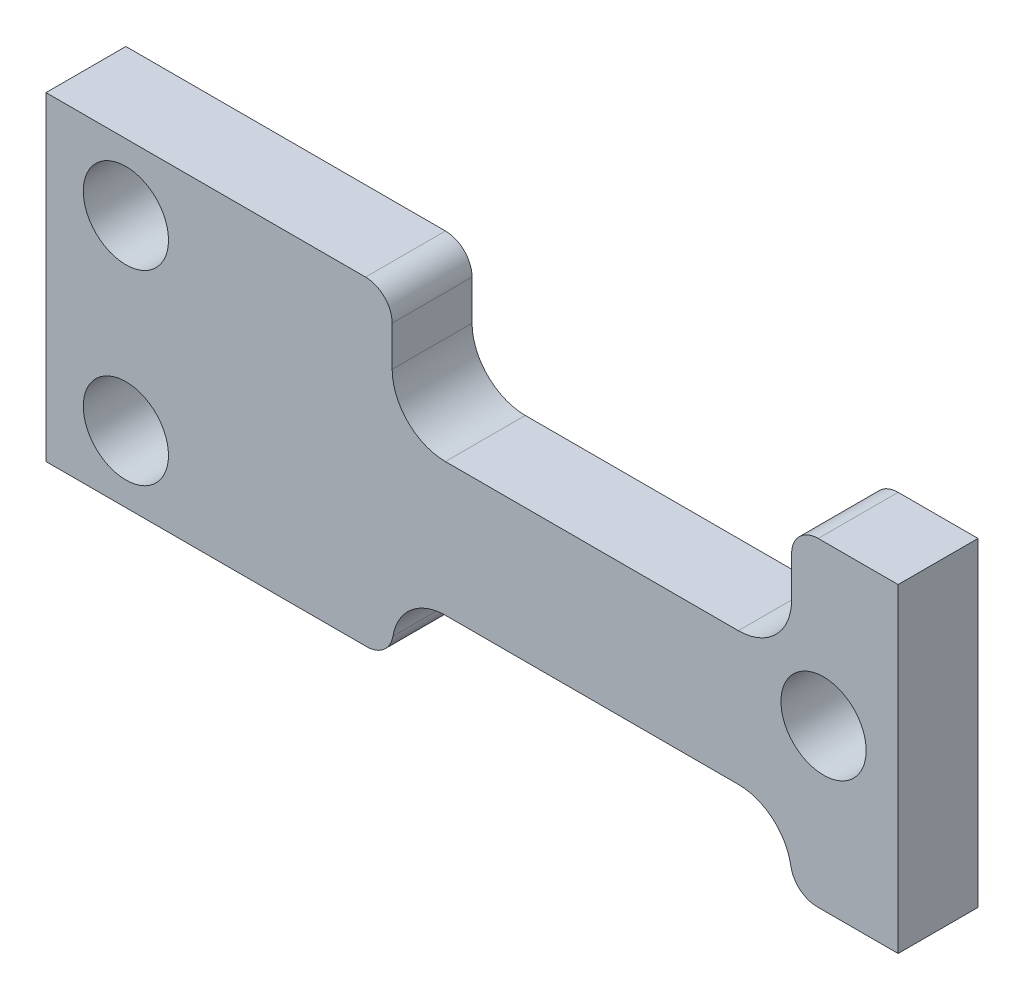
SolidWorks part; units mm, degrees
material "Thornel Mat VMA"
ref_plane "前视基准面" through (0, 0, 0) normal (0, 0, 1) x (1, 0, 0)
ref_plane "上视基准面" through (0, 0, 0) normal (0, 1, 0) x (1, 0, 0)
ref_plane "右视基准面" through (0, 0, 0) normal (1, 0, 0) x (0, 0, -1)
sketch "草图1" plane through (0, 0, 0) normal (0, 0, 1) x (1, 0, 0)
  line L0 (0, 0) -> (0, 26.8)
  line L1 (0, 26.8) -> (12, 26.8)
  line L2 (12, 26.8) -> (12, 29.8)
  line L3 (12, 29.8) -> (22, 29.8)
  line L4 (22, 29.8) -> (22, 26.8)
  line L5 (22, 26.8) -> (32, 26.8)
  line L6 (32, 26.8) -> (32, 0)
  line L7 (32, 0) -> (0, 0)
  line L9 (13, 10) -> (28, 10)
  line L10 (13, 10) -> (13, 4)
  line L11 (13, 4) -> (28, 4)
  line L12 (28, 10) -> (28, 4)
  line L13 (13, 21) -> (28, 21)
  line L14 (13, 21) -> (13, 15)
  line L15 (13, 15) -> (28, 15)
  line L16 (28, 21) -> (28, 15)
  circle A0 centre (3, 17) radius 1.6
  circle A1 centre (3, 10) radius 1.6
  dimension "D4" = 3.2
  dimension "D5" = 3
  dimension "D6" = 9.8
  dimension "D7" = 10
  dimension "D8" = 7
  dimension "D10" = 4
  dimension "D1" = 12
  dimension "D2" = 10
  dimension "D3" = 3
  dimension "D9" = 10
  dimension "D11" = 15
  dimension "D12" = 6
  dimension "D13" = 4
  dimension "D14" = 5
  dimension "D15" = 6
extrude "凸台-拉伸1" add sketch "草图1" along normal blind 3
fillet "圆角1" radius 2 8 edges at (13, 4, 1.5) (28, 4, 1.5) (28, 10, 1.5) (13, 10, 1.5) (28, 15, 1.5) (28, 21, 1.5) (13, 21, 1.5) (13, 15, 1.5)
fillet "圆角2" radius 3 2 edges at (32, 0, 1.5) (0, 0, 1.5)
sketch "草图2" plane through (0, 0, 3) normal (0, 0, 1) x (1, 0, 0)
  line L0 (0, 26.8) -> (0, 3) construction
  line L1 (0, 19.5) -> (32, 19.5)
  line L2 (0, 19.5) -> (0, 31.6123)
  line L3 (0, 31.6123) -> (32, 31.6123)
  line L4 (32, 19.5) -> (32, 31.6123)
  line L5 (32, 3) -> (32, 26.8) construction
  line L6 (3, 17) -> (3, 10) construction
  line L7 (0, 7.5) -> (32, 7.5)
  line L8 (0, 7.5) -> (0, -4.6123)
  line L9 (0, -4.6123) -> (32, -4.6123)
  line L10 (32, 7.5) -> (32, -4.6123)
  line L11 (3, 13.5) -> (38.3804, 13.5) construction
  circle A0 centre (29.2, 13.5) radius 1.6
  dimension "D2" = 3.2
  dimension "D3" = 26.2
  dimension "D1" = 12
extrude "切除-拉伸1" cut sketch "草图2" against normal through all
fillet "圆角3" radius 1 4 edges at (28, 7.5, 1.5) (13, 7.5, 1.5) (13.0635, 19.5, 1.5) (27.9365, 19.5, 1.5)
